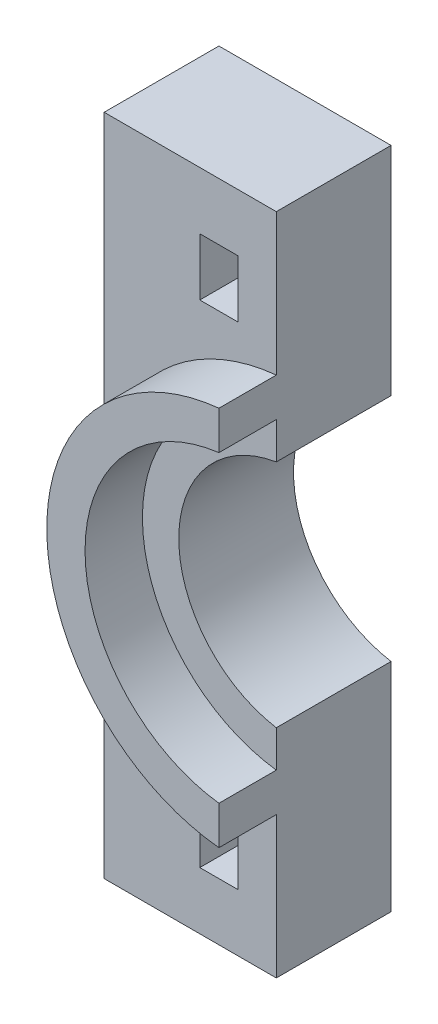
SolidWorks part; units mm, degrees
ref_plane "前基準面" through (0, 0, 0) normal (0, 0, 1) x (1, 0, 0)
ref_plane "上基準面" through (0, 0, 0) normal (0, 1, 0) x (1, 0, 0)
ref_plane "右基準面" through (0, 0, 0) normal (1, 0, 0) x (0, 0, -1)
sketch "草圖1" plane through (0, 0, 0) normal (0, 0, 1) x (1, 0, 0)
  line L1 (-5, 17.35) -> (5, 17.35)
  line L2 (-5, 17.35) -> (-5, -17.35)
  line L3 (-5, -17.35) -> (5, -17.35)
  line L4 (5, 17.35) -> (5, -17.35)
  line L5 (-5, 17.35) -> (5, -17.35) construction
  line L6 (-5, -17.35) -> (5, 17.35) construction
  line L7 (0, -11.35) -> (2, -11.35)
  line L8 (0, -11.35) -> (0, -14.35)
  line L9 (0, -14.35) -> (2, -14.35)
  line L10 (2, -11.35) -> (2, -14.35)
  line L11 (0, -11.35) -> (2, -14.35) construction
  line L12 (0, -14.35) -> (2, -11.35) construction
  line L13 (0, 14.35) -> (2, 14.35)
  line L14 (0, 14.35) -> (0, 11.35)
  line L15 (0, 11.35) -> (2, 11.35)
  line L16 (2, 14.35) -> (2, 11.35)
  line L17 (0, 14.35) -> (2, 11.35) construction
  line L18 (0, 11.35) -> (2, 14.35) construction
  arc A0 (5, 6.1) -> (5, -6.1) centre (5, 0) ccw
  point P0 (0, 0)
  point P7 (1, -12.85)
  point P14 (1, 12.85)
  dimension "D3" = 6.1
  dimension "D1" = 34.7
  dimension "D2" = 10
  dimension "D4" = 2
  dimension "D5" = 3
  dimension "D6" = 3
  dimension "D7" = 3
  dimension "D8" = 2
  dimension "D9" = 3
  dimension "D10" = 3
  dimension "D11" = 3
extrude "填料-伸長1" add sketch "草圖1" along normal blind 6 contours A0 L4 L1 L2 L3 L7 L10 L9 L8 L13 L16 L15 L14
sketch "草圖2" plane through (0, 0, 6) normal (0, 0, 1) x (1, 0, 0)
  line L0 (5, 17.35) -> (5, 6.1) construction
  line L1 (5, -6.1) -> (5, -17.35) construction
  line L2 (5, 10) -> (5, 8)
  line L3 (5, -8) -> (5, -10)
  arc A0 (5, 8) -> (5, -8) centre (5, 0) ccw
  arc A1 (5, -10) -> (5, 10) centre (5, 0) cw
  dimension "D1" = 8
  dimension "D2" = 10
extrude "填料-伸長2" add sketch "草圖2" along normal blind 3
sketch "草圖3" plane through (0, 0, 6) normal (0, 0, 1) x (1, 0, 0)
  line L0 (-5, 17.35) -> (5, 17.35) construction
  line L1 (5, 17.35) -> (4, 17.35)
  line L2 (5, 17.35) -> (5, -17.35)
  line L3 (5, -17.35) -> (4, -17.35)
  line L4 (4, 17.35) -> (4, -17.35)
  line L5 (5, 17.35) -> (5, 10) construction
  line L6 (-5, -17.35) -> (5, -17.35) construction
  dimension "D1" = 1
extrude "除料-伸長1" cut sketch "草圖3" against normal mid plane 18
